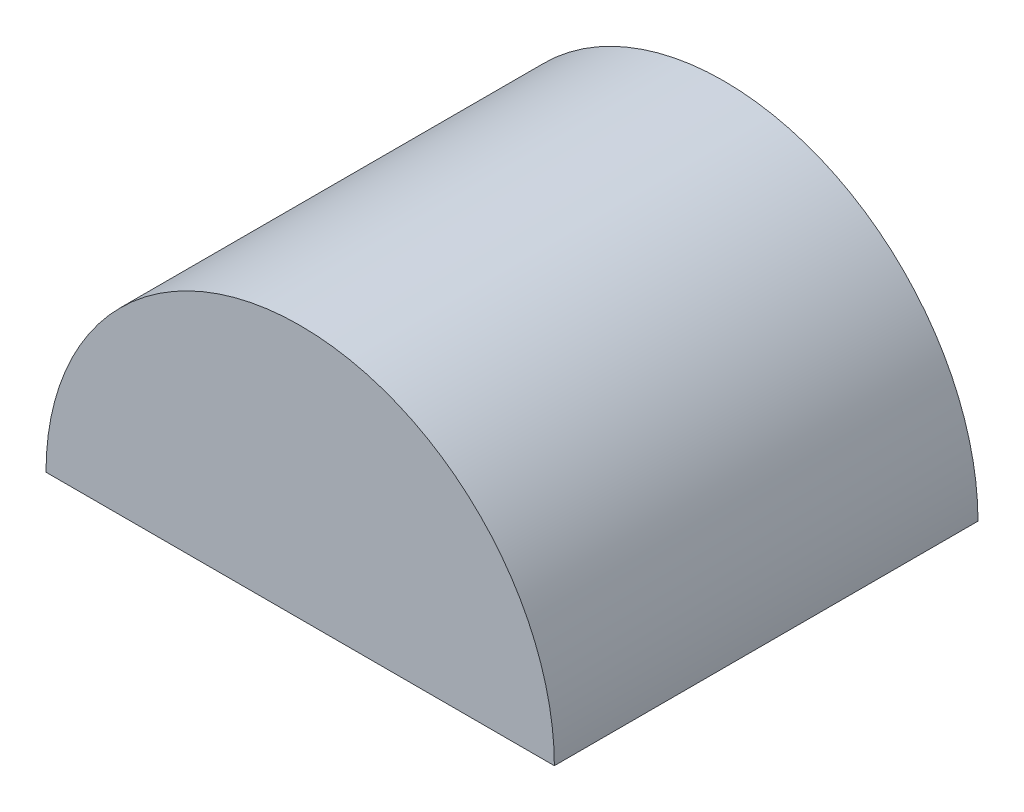
SolidWorks part; units mm, degrees
ref_plane "Front Plane" through (0, 0, 0) normal (0, 0, 1) x (1, 0, 0)
ref_plane "Top Plane" through (0, 0, 0) normal (0, 1, 0) x (1, 0, 0)
ref_plane "Right Plane" through (0, 0, 0) normal (1, 0, 0) x (0, 0, -1)
sketch "Sketch2" plane through (0, 0, 0) normal (0, 0, 1) x (1, 0, 0)
  line L0 (-300, 0) -> (300, 0)
  arc A0 (300, 0) -> (-300, 0) centre (0, 0) ccw
  point P6 (0, 0)
  dimension "D1" = 600
extrude "Boss-Extrude1" add sketch "Sketch2" along normal blind 500
